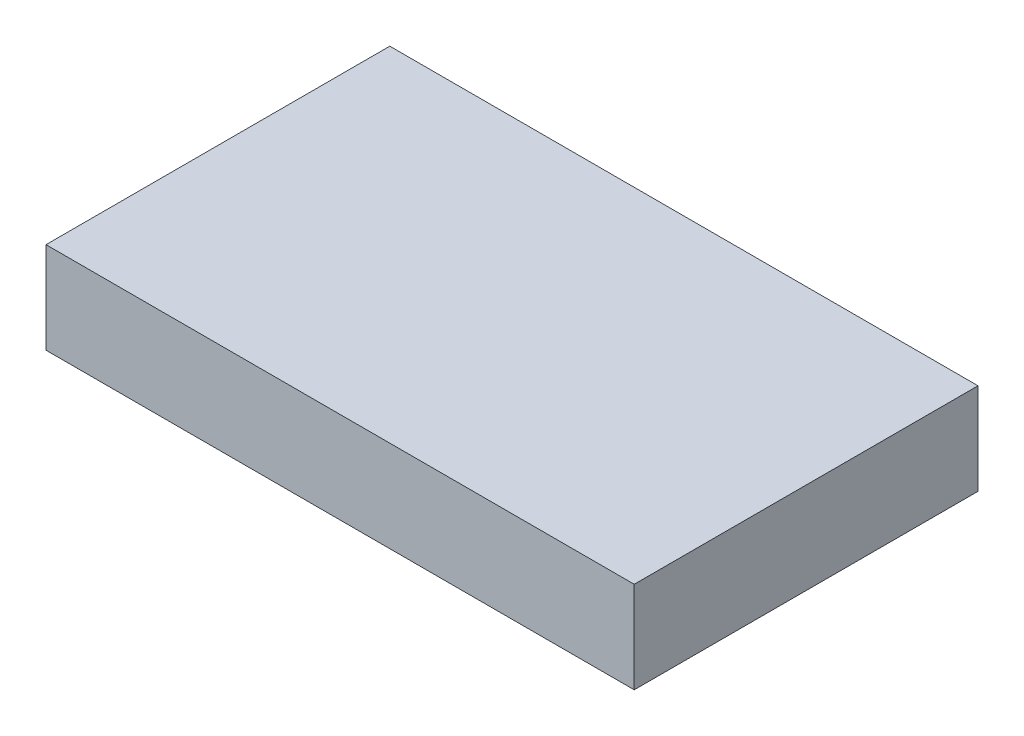
SolidWorks part; units mm, degrees
ref_plane "Front Plane" through (0, 0, 0) normal (0, 0, 1) x (1, 0, 0)
ref_plane "Top Plane" through (0, 0, 0) normal (0, 1, 0) x (1, 0, 0)
ref_plane "Right Plane" through (0, 0, 0) normal (1, 0, 0) x (0, 0, -1)
other "Configuration Table"
sketch "Sketch1" plane through (0, 0, 0) normal (0, 1, 0) x (1, 0, 0)
  line L1 (-71.0027, 38.8596) -> (48.2947, 38.8596)
  line L2 (-71.0027, 38.8596) -> (-71.0027, -30.8638)
  line L3 (-71.0027, -30.8638) -> (48.2947, -30.8638)
  line L4 (48.2947, 38.8596) -> (48.2947, -30.8638)
extrude "Boss-Extrude1" add sketch "Sketch1" along normal blind 18.542
